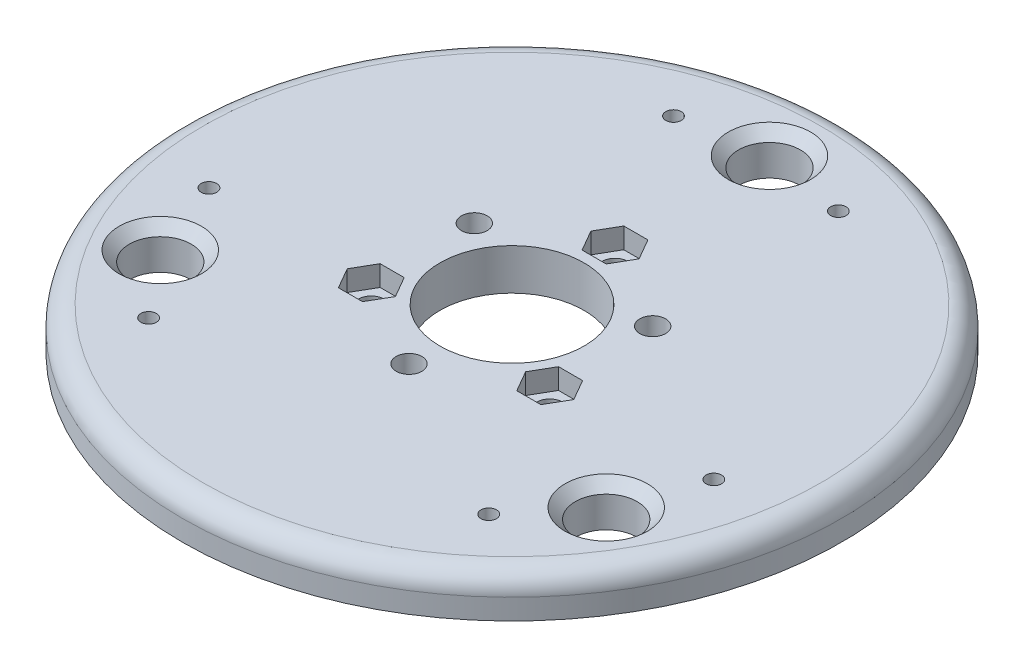
SolidWorks part; units mm, degrees
ref_plane "Спереди" through (0, 0, 0) normal (0, 0, 1) x (1, 0, 0)
ref_plane "Сверху" through (0, 0, 0) normal (0, 1, 0) x (1, 0, 0)
ref_plane "Справа" through (0, 0, 0) normal (1, 0, 0) x (0, 0, -1)
sketch "Эскиз1" plane through (0, 0, 0) normal (0, 1, 0) x (1, 0, 0)
  circle A3 centre (0, 0) radius 32
  circle A4 centre (0, 0) radius 7
  circle A6 centre (0, 0) radius 25 construction
  circle A7 centre (0, 25) radius 3
  circle A8 centre (21.6506, -12.5) radius 3
  circle A9 centre (-21.6506, -12.5) radius 3
  dimension "D4" = 64
  dimension "D1" = 14
  dimension "D2" = 50
  dimension "D3" = 6
  dimension "D5" = 3
extrude "Бобышка-Вытянуть1" add sketch "Эскиз1" along normal blind 4
fillet "Скругление1" radius 2 1 edges at (0, 4, 32)
sketch "Эскиз2" plane through (0, 4, 0) normal (0, 1, 0) x (1, 0, 0)
  circle A0 centre (0, 0) radius 10 construction
  circle A1 centre (0, 10) radius 1.25
  circle A2 centre (8.6603, 5) radius 1.25
  circle A3 centre (8.6603, -5) radius 1.25
  circle A4 centre (0, -10) radius 1.25
  circle A5 centre (-8.6603, -5) radius 1.25
  circle A6 centre (-8.6603, 5) radius 1.25
  dimension "D3" = 6
  dimension "D1" = 20
  dimension "D2" = 2.5
extrude "Вырез-Вытянуть1" cut sketch "Эскиз2" against normal through all
sketch "Эскиз3" plane through (0, 4, 0) normal (0, 1, 0) x (1, 0, 0)
  line L0 (9.8294, -7.025) -> (10.9985, -5)
  line L1 (1.1691, 7.975) -> (2.3383, 10)
  line L2 (2.3383, 10) -> (1.1691, 12.025)
  line L3 (1.1691, 12.025) -> (-1.1691, 12.025)
  line L4 (-1.1691, 12.025) -> (-2.3383, 10)
  line L5 (-2.3383, 10) -> (-1.1691, 7.975)
  line L6 (-1.1691, 7.975) -> (1.1691, 7.975)
  line L7 (10.9985, -5) -> (9.8294, -2.975)
  line L8 (9.8294, -2.975) -> (7.4911, -2.975)
  line L9 (7.4911, -2.975) -> (6.322, -5)
  line L10 (6.322, -5) -> (7.4911, -7.025)
  line L11 (7.4911, -7.025) -> (9.8294, -7.025)
  line L12 (-10.9985, -5) -> (-9.8294, -7.025)
  line L13 (-9.8294, -7.025) -> (-7.4911, -7.025)
  line L14 (-7.4911, -7.025) -> (-6.322, -5)
  line L15 (-6.322, -5) -> (-7.4911, -2.975)
  line L16 (-7.4911, -2.975) -> (-9.8294, -2.975)
  line L17 (-9.8294, -2.975) -> (-10.9985, -5)
  circle A0 centre (0, 10) radius 2.025 construction
  circle A1 centre (8.6603, -5) radius 2.025 construction
  circle A2 centre (-8.6603, -5) radius 2.025 construction
  circle A3 centre (-8.6603, -5) radius 1.25 construction
  point P1 (0, 7.975)
  dimension "D1" = 4.05
  dimension "D2" = 3
extrude "Вырез-Вытянуть2" cut sketch "Эскиз3" against normal blind 2
sketch "Эскиз4" plane through (0, 0, 0) normal (0, -1, 0) x (1, 0, 0)
  line L0 (7.4911, -7.025) -> (9.8294, -7.025)
  line L1 (-1.1691, 7.975) -> (1.1691, 7.975)
  line L2 (1.1691, 7.975) -> (2.3383, 10)
  line L3 (2.3383, 10) -> (1.1691, 12.025)
  line L4 (1.1691, 12.025) -> (-1.1691, 12.025)
  line L5 (-1.1691, 12.025) -> (-2.3383, 10)
  line L6 (-2.3383, 10) -> (-1.1691, 7.975)
  line L7 (9.8294, -7.025) -> (10.9985, -5)
  line L8 (10.9985, -5) -> (9.8294, -2.975)
  line L9 (9.8294, -2.975) -> (7.4911, -2.975)
  line L10 (7.4911, -2.975) -> (6.322, -5)
  line L11 (6.322, -5) -> (7.4911, -7.025)
  line L12 (-9.8294, -2.975) -> (-10.9985, -5)
  line L13 (-10.9985, -5) -> (-9.8294, -7.025)
  line L14 (-9.8294, -7.025) -> (-7.4911, -7.025)
  line L15 (-7.4911, -7.025) -> (-6.322, -5)
  line L16 (-6.322, -5) -> (-7.4911, -2.975)
  line L17 (-7.4911, -2.975) -> (-9.8294, -2.975)
  circle A0 centre (0, 10) radius 2.025 construction
  circle A1 centre (8.6603, -5) radius 2.025 construction
  circle A2 centre (-8.6603, -5) radius 2.025 construction
  circle A3 centre (8.6603, -5) radius 1.25 construction
  dimension "D1" = 4.05
  dimension "D2" = 3
extrude "Вырез-Вытянуть3" cut sketch "Эскиз4" against normal blind 2
chamfer "Фаска1" distance 1 angle 45 3 edges at (0, 4, -22) (-21.6506, 4, 15.5) (21.6506, 4, 15.5)
sketch "Эскиз5" plane through (0, 4, 0) normal (0, 1, 0) x (1, 0, 0)
  line L0 (0, 0) -> (0, 25) construction
  line L1 (-8, 23.6854) -> (8, 23.6854) construction
  circle A0 centre (0, 0) radius 25 construction
  circle A1 centre (8, 23.6854) radius 0.75
  circle A2 centre (-8, 23.6854) radius 0.75
  circle A3 centre (24.5122, -4.9145) radius 0.75
  circle A4 centre (16.5122, -18.7709) radius 0.75
  circle A5 centre (-16.5122, -18.7709) radius 0.75
  circle A6 centre (-24.5122, -4.9145) radius 0.75
  dimension "D2" = 1.5
  dimension "D3" = 1.5
  dimension "D1" = 16
  dimension "D4" = 3
extrude "Вырез-Вытянуть4" cut sketch "Эскиз5" against normal through all
equation "\"motor_diameter\"= 30"
equation "\"mm_diameter\"= IIF ( \"motor_diameter\" < 34 , 41 , \"motor_diameter\" + 8 )"
equation "\"upper_shafts_diameter\"= 5"
equation "\"upper_shats_length\"= 180"
equation "\"upper_bearing_d1\"= 10"
equation "\"upper_bearing_d2\"= 5"
equation "\"upper_bearing_h\"= 15"
equation "\"lower_shafts_diameter\"= 5"
equation "\"lower_shafts_length\"= 180"
equation "\"lower_bearing_d1\"= 10"
equation "\"lower_bearing_d2\"= 5"
equation "\"lower_bearing_h\"= 15"
equation "\"print_offset\"= 0.5"
equation "\"bh_screws_d\"= 2"
equation "\"bh_screws_h\"= 20"
equation "\"bh_screws_hh_d\"= 3.4"
equation "\"bh_screws_hh_h\"= 2"
equation "\"bh_nut_d\"= 3.8"
equation "\"bh_nut_h\"= 2"
equation "\"motor_screws_d\"= 3"
equation "\"motor_screws_h\"= 16"
equation "\"motor_screws_hh_d\"= 5.5"
equation "\"motor_screws_hh_h\"= 3"
equation "\"plate_hole_distance\"= 25.4"
equation "\"plate_screws_d\"= 6.5"
equation "\"shafts_diameter\"= IIF ( \"mm_diameter\" < 42 , 42 + 8 , \"mm_diameter\" + 8 )"
equation "\"D4@Эскиз1\"= \"system_radius\" * 2"
equation "\"central_hole_diameter\"= 8"
equation "\"bh_thikness\"= 4"
equation "\"D2@Эскиз1\"=\"shafts_diameter\""
equation "\"D3@Эскиз1\"= \"lower_shafts_diameter\" + 1"
equation "\"D1@Бобышка-Вытянуть1\"=\"bh_thikness\""
equation "\"D2@Эскиз2\"=\"bh_screws_d\"+\"print_offset\""
equation "\"D1@Эскиз3\"=\"bh_nut_d\"+\"print_offset\"/2"
equation "\"D1@Вырез-Вытянуть2\"=\"bh_nut_h\""
equation "\"D1@Эскиз4\"=\"bh_nut_d\"+\"print_offset\"/2"
equation "\"D1@Вырез-Вытянуть3\"=\"bh_nut_h\""
equation "\"D2@Эскиз5\"=\"bh_screws_d\"-\"print_offset\""
equation "\"D3@Эскиз5\"=\"D2@Эскиз5\""
equation "\"ends_screws_d\"= 4"
equation "\"ends_screws_h\"= 16"
equation "\"ends_screws_hh_d\"= 6.7"
equation "\"ends_screws_hh_h\"= 4.1"
equation "\"ends_nut_d\"= 6.8"
equation "\"ends_nut_h\"= 3"
equation "\"system_radius\" = ( \"shafts_diameter\" + 12 + \"bh_thikness\" / 2 ) / 2"
equation "\"encoder_distance\"= \"system_radius\" + 4"
equation "\"tape_position\"= \"encoder_distance\" - 2 + 3.9 + 1.7 / 2"
